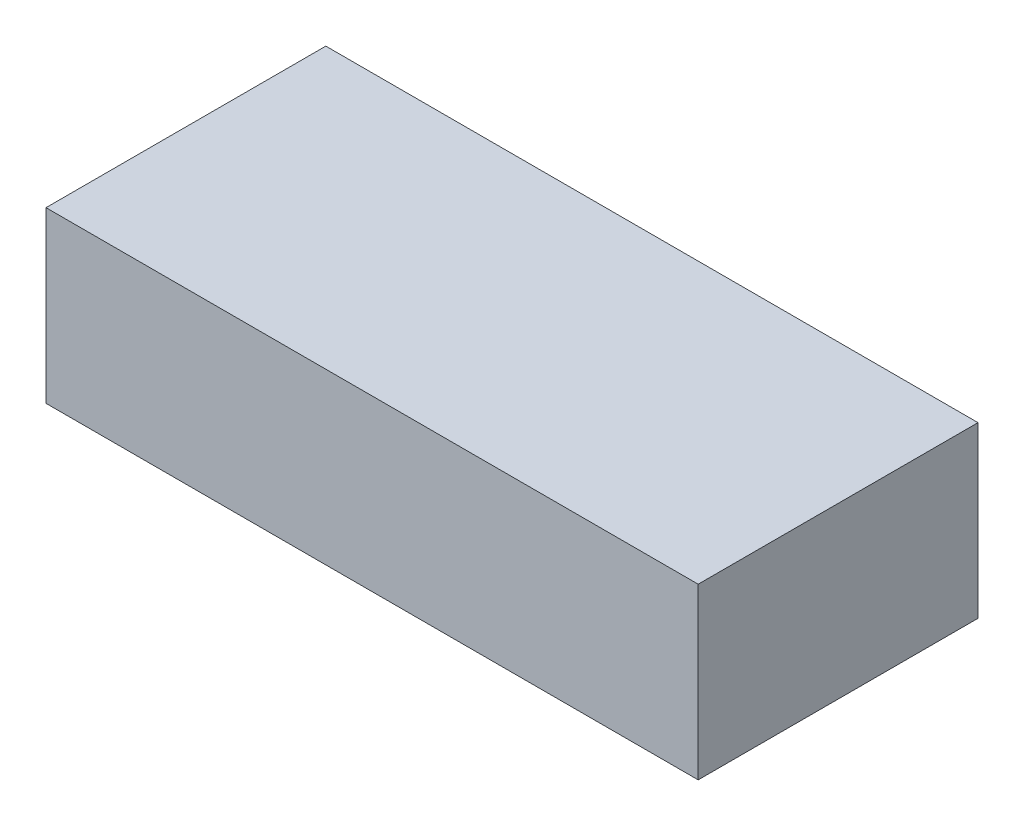
SolidWorks part; units mm, degrees
ref_plane "Front Plane" through (0, 0, 0) normal (0, 0, 1) x (1, 0, 0)
ref_plane "Top Plane" through (0, 0, 0) normal (0, 1, 0) x (1, 0, 0)
ref_plane "Right Plane" through (0, 0, 0) normal (1, 0, 0) x (0, 0, -1)
sketch "Sketch1" plane through (0, 0, 0) normal (0, 1, 0) x (1, 0, 0)
  line L1 (-38.481, -16.51) -> (38.481, -16.51)
  line L2 (-38.481, -16.51) -> (-38.481, 16.51)
  line L3 (-38.481, 16.51) -> (38.481, 16.51)
  line L4 (38.481, -16.51) -> (38.481, 16.51)
  line L5 (-38.481, -16.51) -> (38.481, 16.51) construction
  line L6 (-38.481, 16.51) -> (38.481, -16.51) construction
  point P0 (0, 0)
  dimension "D1" = 76.962
  dimension "D2" = 33.02
extrude "Boss-Extrude1" add sketch "Sketch1" along normal blind 20
